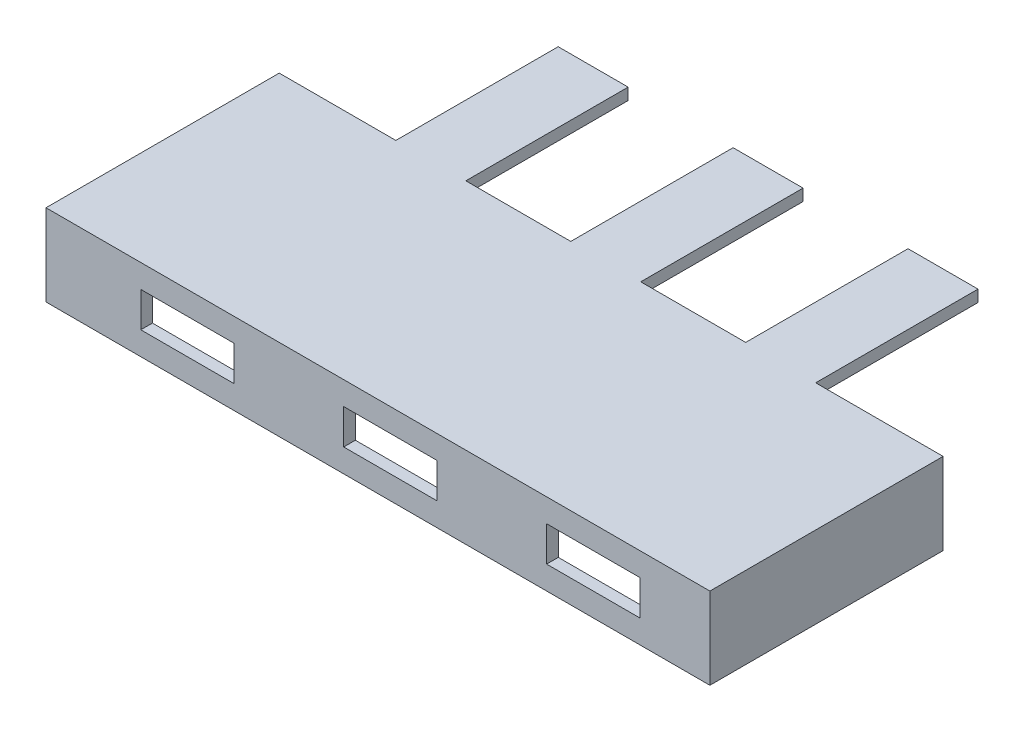
SolidWorks part; units mm, degrees
ref_plane "前视基准面" through (0, 0, 0) normal (0, 0, 1) x (1, 0, 0)
ref_plane "上视基准面" through (0, 0, 0) normal (0, 1, 0) x (1, 0, 0)
ref_plane "右视基准面" through (0, 0, 0) normal (1, 0, 0) x (0, 0, -1)
sketch "草图1" plane through (0, 0, 0) normal (0, 1, 0) x (1, 0, 0)
  line L1 (-52.5156, -40.384) -> (-52.5156, 29.212)
  line L2 (-52.5156, 29.212) -> (-82.5156, 29.212)
  line L3 (-82.5156, 29.212) -> (-82.5156, -40.384)
  line L5 (-127.5156, -40.384) -> (-127.5156, 29.212)
  line L6 (-127.5156, 29.212) -> (-157.5156, 29.212)
  line L7 (-157.5156, 29.212) -> (-157.5156, -40.384)
  line L8 (-232.5156, 29.212) -> (-232.5156, -40.384)
  line L9 (-202.5156, 29.212) -> (-232.5156, 29.212)
  line L10 (-202.5156, -40.384) -> (-202.5156, 29.212)
  line L12 (-282.5156, -40.384) -> (-232.5156, -40.384)
  line L13 (-232.5156, -40.384) -> (-232.5156, 29.212)
  line L14 (-232.5156, 29.212) -> (-202.5156, 29.212)
  line L15 (-202.5156, 29.212) -> (-202.5156, -40.384)
  line L16 (-202.5156, -40.384) -> (-157.5156, -40.384)
  line L17 (-157.5156, -40.384) -> (-157.5156, 29.212)
  line L18 (-157.5156, 29.212) -> (-127.5156, 29.212)
  line L19 (-127.5156, 29.212) -> (-127.5156, -40.384)
  line L20 (-127.5156, -40.384) -> (-82.5156, -40.384)
  line L21 (-82.5156, -40.384) -> (-82.5156, 29.212)
  line L22 (-82.5156, 29.212) -> (-52.5156, 29.212)
  line L23 (-52.5156, 29.212) -> (-52.5156, -40.384)
  line L24 (-52.5156, -40.384) -> (2.1255, -40.384)
  line L28 (-282.5156, -40.384) -> (-282.5156, -140.384)
  line L29 (-282.5156, -140.384) -> (2.1255, -140.384)
  line L30 (2.1255, -140.384) -> (2.1255, -40.384)
  dimension "D2" = 100
sketch "草图2" plane through (0, 0, 0) normal (0, 1, 0) x (1, 0, 0)
  line L25 (-232.5156, 29.212) -> (-232.5156, -40.384)
  line L26 (-232.5156, -40.384) -> (-282.5156, -40.384)
  line L27 (-282.5156, -40.384) -> (-282.5156, -140.384)
  line L28 (-282.5156, -140.384) -> (2.1255, -140.384)
  line L29 (2.1255, -140.384) -> (2.1255, -40.384)
  line L30 (2.1255, -40.384) -> (-52.5156, -40.384)
  line L31 (-52.5156, -40.384) -> (-52.5156, 29.212)
  line L32 (-52.5156, 29.212) -> (-82.5156, 29.212)
  line L33 (-82.5156, 29.212) -> (-82.5156, -40.384)
  line L34 (-82.5156, -40.384) -> (-127.5156, -40.384)
  line L35 (-127.5156, -40.384) -> (-127.5156, 29.212)
  line L36 (-127.5156, 29.212) -> (-157.5156, 29.212)
  line L37 (-157.5156, 29.212) -> (-157.5156, -40.384)
  line L44 (-157.5156, -40.384) -> (-202.5156, -40.384)
  line L47 (-202.5156, -40.384) -> (-202.5156, 29.212)
  line L48 (-202.5156, 29.212) -> (-232.5156, 29.212)
extrude "凸台-拉伸1" add sketch "草图2" along normal blind 5
sketch "草图3" plane through (0, 5, 0) normal (0, 1, 0) x (1, 0, 0)
  line L1 (-282.5156, -140.384) -> (2.1255, -140.384)
  line L6 (-282.5156, -40.384) -> (-262.5156, -40.384)
  line L7 (-282.5156, -40.384) -> (-282.5156, -60.384)
  line L8 (-282.5156, -60.384) -> (-262.5156, -60.384)
  line L9 (-262.5156, -40.384) -> (-262.5156, -60.384)
  line L22 (2.1255, -140.384) -> (2.1255, -40.384)
  line L24 (-277.5156, -45.384) -> (-267.5156, -45.384)
  line L25 (-277.5156, -45.384) -> (-277.5156, -55.384)
  line L26 (-277.5156, -55.384) -> (-267.5156, -55.384)
  line L27 (-267.5156, -45.384) -> (-267.5156, -55.384)
  line L29 (-267.5156, -135.384) -> (-267.5156, -125.384)
  line L30 (-277.5156, -125.384) -> (-267.5156, -125.384)
  line L31 (-277.5156, -135.384) -> (-277.5156, -125.384)
  line L32 (-277.5156, -135.384) -> (-267.5156, -135.384)
  line L33 (-262.5156, -140.384) -> (-262.5156, -120.384)
  line L34 (-282.5156, -120.384) -> (-262.5156, -120.384)
  line L35 (-282.5156, -140.384) -> (-282.5156, -120.384)
  line L36 (-282.5156, -140.384) -> (-262.5156, -140.384)
  line L37 (2.1255, -140.384) -> (-17.8745, -140.384)
  line L38 (2.1255, -140.384) -> (2.1255, -120.384)
  line L39 (2.1255, -120.384) -> (-17.8745, -120.384)
  line L40 (-17.8745, -140.384) -> (-17.8745, -120.384)
  line L41 (-2.8745, -135.384) -> (-12.8745, -135.384)
  line L42 (-2.8745, -135.384) -> (-2.8745, -125.384)
  line L43 (-2.8745, -125.384) -> (-12.8745, -125.384)
  line L44 (-12.8745, -135.384) -> (-12.8745, -125.384)
  line L45 (-12.8745, -45.384) -> (-12.8745, -55.384)
  line L46 (-2.8745, -55.384) -> (-12.8745, -55.384)
  line L47 (-2.8745, -45.384) -> (-2.8745, -55.384)
  line L48 (-2.8745, -45.384) -> (-12.8745, -45.384)
  line L49 (-17.8745, -40.384) -> (-17.8745, -60.384)
  line L50 (2.1255, -60.384) -> (-17.8745, -60.384)
  line L51 (2.1255, -40.384) -> (2.1255, -60.384)
  line L52 (2.1255, -40.384) -> (-17.8745, -40.384)
  point P16 (-272.5156, -50.384)
  point P23 (-272.5156, -130.384)
  point P43 (-7.8745, -130.384)
  point P44 (-7.8745, -50.384)
  dimension "D1" = 20
  dimension "D5" = 20
  dimension "D9" = 10
  dimension "D10" = 10
sketch "草图4" plane through (0, 5, 0) normal (0, 1, 0) x (1, 0, 0)
  line L1 (-262.5156, -60.384) -> (-282.5156, -60.384)
  line L2 (-262.5156, -60.384) -> (-262.5156, -40.384)
  line L3 (-262.5156, -40.384) -> (-282.5156, -40.384)
  line L4 (-282.5156, -60.384) -> (-282.5156, -40.384)
  line L5 (-267.5156, -55.384) -> (-277.5156, -55.384)
  line L6 (-267.5156, -55.384) -> (-267.5156, -45.384)
  line L7 (-267.5156, -45.384) -> (-277.5156, -45.384)
  line L8 (-277.5156, -55.384) -> (-277.5156, -45.384)
  line L9 (-262.5156, -140.384) -> (-282.5156, -140.384)
  line L10 (-262.5156, -140.384) -> (-262.5156, -120.384)
  line L11 (-262.5156, -120.384) -> (-282.5156, -120.384)
  line L12 (-282.5156, -140.384) -> (-282.5156, -120.384)
  line L13 (-267.5156, -135.384) -> (-277.5156, -135.384)
  line L14 (-267.5156, -135.384) -> (-267.5156, -125.384)
  line L15 (-267.5156, -125.384) -> (-277.5156, -125.384)
  line L16 (-277.5156, -135.384) -> (-277.5156, -125.384)
  line L17 (-17.8745, -40.384) -> (2.1255, -40.384)
  line L18 (-17.8745, -40.384) -> (-17.8745, -60.384)
  line L19 (-17.8745, -60.384) -> (2.1255, -60.384)
  line L20 (2.1255, -40.384) -> (2.1255, -60.384)
  line L21 (-12.8745, -45.384) -> (-2.8745, -45.384)
  line L22 (-12.8745, -45.384) -> (-12.8745, -55.384)
  line L23 (-12.8745, -55.384) -> (-2.8745, -55.384)
  line L24 (-2.8745, -45.384) -> (-2.8745, -55.384)
  line L25 (-17.8745, -120.384) -> (2.1255, -120.384)
  line L26 (-17.8745, -120.384) -> (-17.8745, -140.384)
  line L27 (-17.8745, -140.384) -> (2.1255, -140.384)
  line L28 (2.1255, -120.384) -> (2.1255, -140.384)
  line L29 (-12.8745, -125.384) -> (-2.8745, -125.384)
  line L30 (-12.8745, -125.384) -> (-12.8745, -135.384)
  line L31 (-12.8745, -135.384) -> (-2.8745, -135.384)
  line L32 (-2.8745, -125.384) -> (-2.8745, -135.384)
extrude "凸台-拉伸2" add sketch "草图4" against normal blind 35
sketch "草图5" plane through (0, 0, 0) normal (0, -1, 0) x (1, 0, 0)
  line L0 (-282.5156, 60.384) -> (-262.5156, 60.384) construction
  line L1 (-17.8745, 140.384) -> (-262.7493, 140.384)
  line L2 (-17.8745, 140.384) -> (-17.8745, 135.384)
  line L3 (-17.8745, 135.384) -> (-262.7493, 135.384)
  line L4 (-262.7493, 140.384) -> (-262.7493, 135.384)
  line L5 (-282.5156, 120.384) -> (-277.5156, 120.384)
  line L6 (-282.5156, 120.384) -> (-282.5156, 60.384)
  line L7 (-282.5156, 60.384) -> (-277.5156, 60.384)
  line L8 (-277.5156, 120.384) -> (-277.5156, 60.384)
  line L9 (2.1255, 120.384) -> (-17.8745, 120.384) construction
  line L10 (2.1255, 60.384) -> (-2.8745, 60.384)
  line L11 (2.1255, 60.384) -> (2.1255, 120.384)
  line L12 (2.1255, 120.384) -> (-2.8745, 120.384)
  line L13 (-2.8745, 60.384) -> (-2.8745, 120.384)
  dimension "D1" = 5
  dimension "D2" = 5
  dimension "D3" = 5
extrude "凸台-拉伸3" add sketch "草图5" along normal blind 30
sketch "草图6" plane through (0, 0, 0) normal (0, -1, 0) x (1, 0, 0)
  line L0 (-2.8745, 55.384) -> (-2.8745, 45.384) construction
  line L1 (-12.8745, 45.384) -> (-12.8745, 55.384) construction
  line L2 (-2.8745, 45.384) -> (-12.8745, 45.384) construction
  line L3 (-12.8745, 55.384) -> (-2.8745, 55.384) construction
  line L4 (-2.8745, 55.384) -> (-2.8745, 45.384)
  line L5 (-12.8745, 45.384) -> (-12.8745, 55.384)
  line L6 (-2.8745, 45.384) -> (-12.8745, 45.384)
  line L7 (-12.8745, 55.384) -> (-2.8745, 55.384)
  line L8 (-2.8745, 135.384) -> (-12.8745, 135.384) construction
  line L9 (-2.8745, 125.384) -> (-12.8745, 125.384) construction
  line L10 (-12.8745, 125.384) -> (-12.8745, 135.384) construction
  line L11 (-12.8745, 135.384) -> (-2.8745, 135.384) construction
  line L12 (-2.8745, 135.384) -> (-12.8745, 135.384)
  line L13 (-2.8745, 125.384) -> (-12.8745, 125.384)
  line L14 (-12.8745, 125.384) -> (-12.8745, 135.384)
  line L15 (-12.8745, 135.384) -> (-2.8745, 135.384)
  line L16 (-262.5156, 40.384) -> (-262.5156, 60.384)
  line L17 (-262.5156, 60.384) -> (-277.5156, 60.384)
  line L18 (-277.5156, 60.384) -> (-277.5156, 120.384)
  line L19 (-277.5156, 120.384) -> (-262.5156, 120.384)
  line L20 (-262.5156, 120.384) -> (-262.5156, 135.384)
  line L21 (-262.5156, 135.384) -> (-17.8745, 135.384)
  line L22 (-17.8745, 135.384) -> (-17.8745, 120.384)
  line L23 (-17.8745, 120.384) -> (-2.8745, 120.384)
  line L24 (-2.8745, 120.384) -> (-2.8745, 60.384)
  line L25 (-2.8745, 60.384) -> (-17.8745, 60.384)
  line L26 (-17.8745, 60.384) -> (-17.8745, 40.384)
  line L27 (-17.8745, 40.384) -> (2.1255, 40.384)
  line L28 (2.1255, 40.384) -> (2.1255, 140.384)
  line L29 (2.1255, 140.384) -> (-282.5156, 140.384)
  line L30 (-282.5156, 140.384) -> (-282.5156, 40.384)
  line L31 (-282.5156, 40.384) -> (-262.5156, 40.384)
  line L32 (-262.5156, 40.384) -> (-262.5156, 60.384)
  line L33 (-262.5156, 60.384) -> (-277.5156, 60.384)
  line L34 (-277.5156, 60.384) -> (-277.5156, 120.384)
  line L35 (-277.5156, 120.384) -> (-262.5156, 120.384)
  line L36 (-262.5156, 120.384) -> (-262.5156, 135.384)
  line L37 (-262.5156, 135.384) -> (-17.8745, 135.384)
  line L38 (-17.8745, 135.384) -> (-17.8745, 120.384)
  line L39 (-17.8745, 120.384) -> (-2.8745, 120.384)
  line L40 (-2.8745, 120.384) -> (-2.8745, 60.384)
  line L41 (-2.8745, 60.384) -> (-17.8745, 60.384)
  line L42 (-17.8745, 60.384) -> (-17.8745, 40.384)
  line L43 (-17.8745, 40.384) -> (2.1255, 40.384)
  line L44 (2.1255, 40.384) -> (2.1255, 140.384)
  line L45 (2.1255, 140.384) -> (-282.5156, 140.384)
  line L46 (-282.5156, 140.384) -> (-282.5156, 40.384)
  line L47 (-282.5156, 40.384) -> (-262.5156, 40.384)
  line L48 (-2.8745, 125.384) -> (-2.8745, 135.384)
  line L50 (-267.5156, 45.384) -> (-277.5156, 45.384)
  line L51 (-267.5156, 45.384) -> (-267.5156, 55.384)
  line L52 (-267.5156, 55.384) -> (-277.5156, 55.384)
  line L53 (-277.5156, 45.384) -> (-277.5156, 55.384)
  line L54 (-277.5156, 135.384) -> (-267.5156, 135.384)
  line L55 (-277.5156, 135.384) -> (-277.5156, 125.384)
  line L56 (-277.5156, 125.384) -> (-267.5156, 125.384)
  line L57 (-267.5156, 135.384) -> (-267.5156, 125.384)
  dimension "D1" = 0
sketch "草图7" plane through (0, 0, 140.384) normal (0, 0, 1) x (1, 0, 0)
  line L0 (-114.8745, -20) -> (-114.8745, -5)
  line L13 (-27.8745, -20) -> (-67.8745, -20)
  line L14 (-27.8745, -20) -> (-27.8745, -5)
  line L15 (-27.8745, -5) -> (-67.8745, -5)
  line L16 (-67.8745, -20) -> (-67.8745, -5)
  line L17 (-114.8745, -20) -> (-154.8745, -20)
  line L18 (-154.8745, -20) -> (-154.8745, -5)
  line L19 (-114.8745, -5) -> (-154.8745, -5)
  line L20 (-201.8745, -20) -> (-201.8745, -5)
  line L21 (-201.8745, -20) -> (-241.8745, -20)
  line L22 (-241.8745, -20) -> (-241.8745, -5)
  line L23 (-201.8745, -5) -> (-241.8745, -5)
  dimension "D2" = 40
  dimension "D5" = 3
extrude "切除-拉伸2" cut sketch "草图7" against normal up to surface (5 mm away) up to face at (-140.1951, -15, 135.384)
